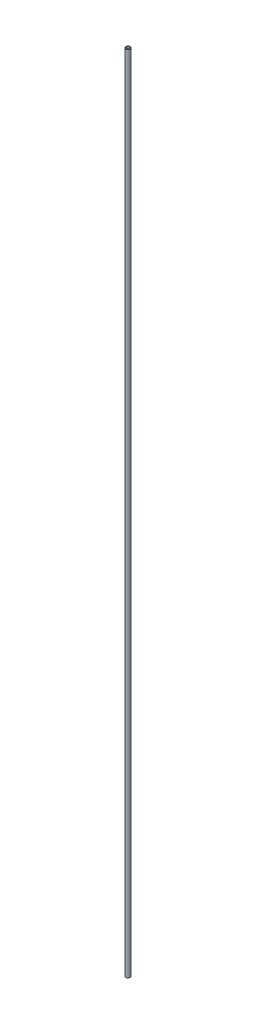
SolidWorks part; units mm, degrees
material "AISI 304"
ref_plane "Front Plane" through (0, 0, 0) normal (0, 0, 1) x (1, 0, 0)
ref_plane "Top Plane" through (0, 0, 0) normal (0, 1, 0) x (1, 0, 0)
ref_plane "Right Plane" through (0, 0, 0) normal (1, 0, 0) x (0, 0, -1)
sketch "Sketch1" plane through (0, 0, 0) normal (0, 1, 0) x (1, 0, 0)
  circle A0 centre (0, 0) radius 24.13
  circle A1 centre (0, 0) radius 19.05
extrude "Boss-Extrude1" add sketch "Sketch1" along normal blind 9144
